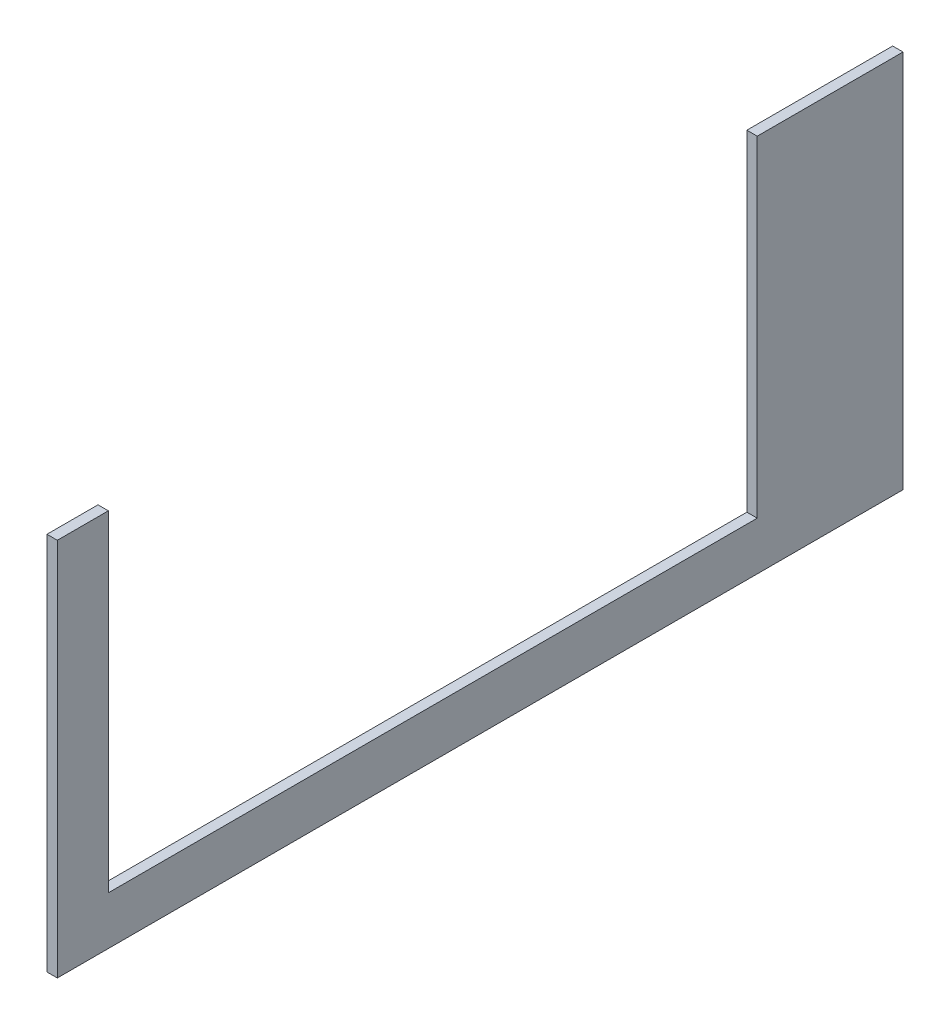
SolidWorks part; units mm, degrees
material "E-Glass Fiber"
ref_plane "Front Plane" through (0, 0, 0) normal (0, 0, 1) x (1, 0, 0)
ref_plane "Top Plane" through (0, 0, 0) normal (0, 1, 0) x (1, 0, 0)
ref_plane "Right Plane" through (0, 0, 0) normal (1, 0, 0) x (0, 0, -1)
sketch "Sketch1" plane through (0, 0, 0) normal (1, 0, 0) x (0, 0, 1)
  line L0 (0, -747.3382) -> (0, -299.7147) construction
  line L1 (0, -3.9116) -> (0, 3.9116) construction
  line L2 (-480, -260) -> (-580, -260)
  line L4 (-3381.666, 0) -> (-1328.9091, 0) construction
  line L5 (-580, -260) -> (-580, 0)
  line L6 (0, -260) -> (-35, -260)
  line L7 (0, -260) -> (0, 0)
  line L8 (0, 0) -> (-580, 0)
  line L10 (-3.9116, 0) -> (3.9116, 0) construction
  line L11 (-35, -260) -> (-35, -33.112)
  line L12 (-35, -33.112) -> (-480, -33.112)
  line L13 (-480, -260) -> (-480, -33.112)
  dimension "D1" = 580
  dimension "D2" = 260
  dimension "D3" = 33.112
  dimension "D4" = 35
  dimension "D5" = 100
extrude "Boss-Extrude1" add sketch "Sketch1" along normal mid plane 7.112
